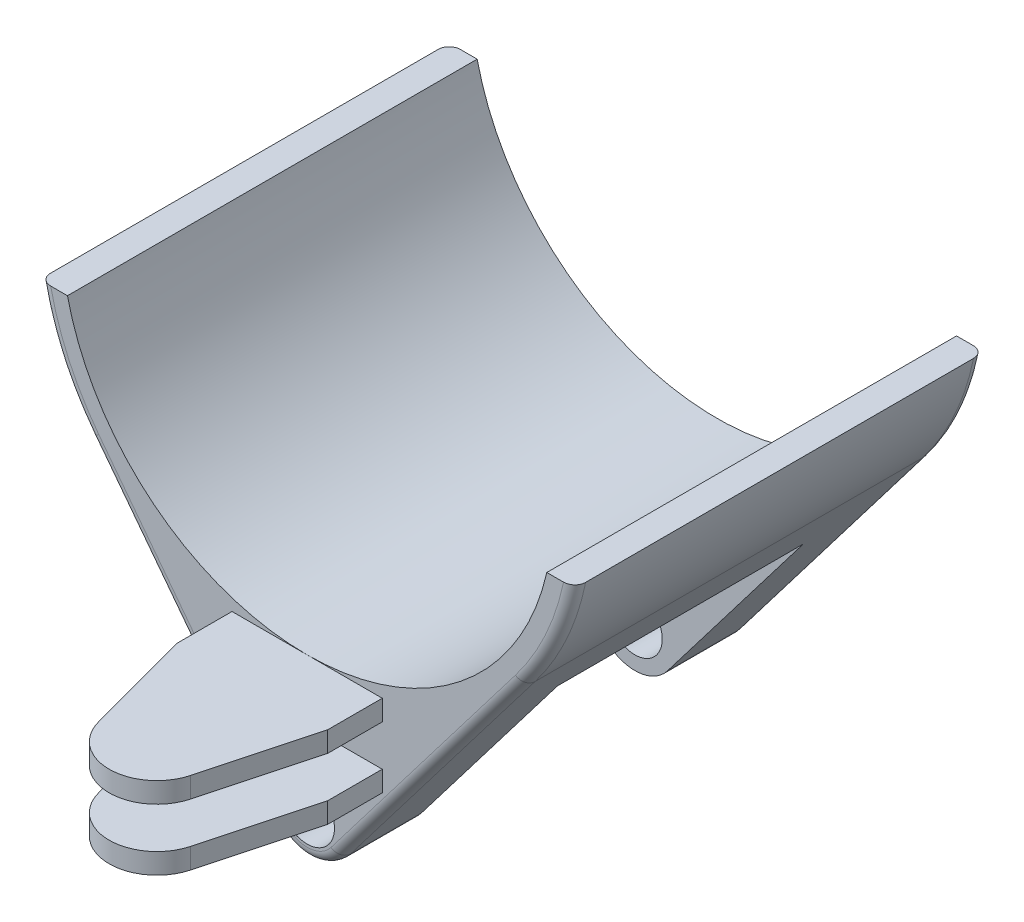
SolidWorks part; units mm, degrees
ref_plane "Front Plane" through (0, 0, 0) normal (0, 0, 1) x (1, 0, 0)
ref_plane "Top Plane" through (0, 0, 0) normal (0, 1, 0) x (1, 0, 0)
ref_plane "Right Plane" through (0, 0, 0) normal (1, 0, 0) x (0, 0, -1)
sketch "Sketch1" plane through (0, 0, 0) normal (0, 0, 1) x (1, 0, 0)
  line L0 (0, 0) -> (0, 420) construction
  line L1 (238.3778, 237.8571) -> (35.7567, -27.3214)
  line L2 (-35.7567, -27.3214) -> (-238.3778, 237.8571)
  line L3 (293.9388, 360) -> (263.2489, 360)
  line L4 (-263.2489, 360) -> (-293.9388, 360)
  arc A0 (-293.9388, 360) -> (-238.3778, 237.8571) centre (0, 420) ccw
  arc A1 (-263.2489, 360) -> (263.2489, 360) centre (0, 420) ccw
  arc A2 (-35.7567, -27.3214) -> (35.7567, -27.3214) centre (0, 0) ccw
  circle A3 centre (0, 0) radius 30
  arc A4 (238.3778, 237.8571) -> (293.9388, 360) centre (0, 420) ccw
  dimension "D1" = 600
  dimension "D2" = 540
  dimension "D3" = 60
  dimension "D4" = 90
  dimension "D5" = 60
  dimension "D6" = 360
extrude "Boss-Extrude2" add sketch "Sketch1" along normal mid plane 450
sketch "Sketch2" plane through (0, 0, 0) normal (0, 1, 0) x (1, 0, 0)
  line L0 (0, -225) -> (0, -390) construction
  line L1 (-263.2489, -225) -> (263.2489, -225) construction
  line L2 (82.5, -225) -> (-82.5, -225)
  line L3 (82.5, -225) -> (82.5, -285)
  line L4 (82.5, -285) -> (50.7097, -403.5933)
  line L5 (-82.5, -225) -> (-82.5, -285)
  line L6 (-82.5, -285) -> (-50.7097, -403.5933)
  arc A0 (-50.7097, -403.5933) -> (50.7097, -403.5933) centre (0, -390) ccw
  point P8 (0, -225)
  dimension "D1" = 165
  dimension "D5" = 105
  dimension "D2" = 60
  dimension "D3" = 60
  dimension "D4" = 165
extrude "Boss-Extrude3" add sketch "Sketch2" along normal blind 90 from offset 60
sketch "Sketch3" plane through (0, 0, 0) normal (1, 0, 0) x (0, 0, -1)
  line L0 (-225, 150) -> (-225, 60) construction
  line L1 (-225, 127.5) -> (-482.4052, 127.5)
  line L2 (-225, 127.5) -> (-225, 82.5)
  line L3 (-225, 82.5) -> (-482.4052, 82.5)
  line L4 (-482.4052, 127.5) -> (-482.4052, 82.5)
  line L5 (-403.5933, 150) -> (-442.5, 150) construction
  dimension "D1" = 45
  dimension "D2" = 22.5
extrude "Cut-Extrude1" cut sketch "Sketch3" against normal mid plane 303.8
sketch "Sketch4" plane through (0, 0, 0) normal (1, 0, 0) x (0, 0, -1)
  line L0 (-225, -27.3214) -> (-225, 237.8571) construction
  line L1 (-135, 142.5) -> (135, 142.5)
  line L2 (-135, 142.5) -> (-135, -224.9)
  line L3 (-135, -224.9) -> (135, -224.9)
  line L4 (135, 142.5) -> (135, -224.9)
  line L5 (-285, 150) -> (-225, 150) construction
  dimension "D1" = 90
  dimension "D2" = 90
  dimension "D3" = 7.5
extrude "Cut-Extrude2" cut sketch "Sketch4" against normal mid plane 843.7
chamfer "Chamfer1" distance 6 angle 45 2 edges at (165.5161, 142.5, 0) (-165.5161, 142.5, 0)
fillet "Fillet1" radius 6 2 edges at (0, 142.5, -135) (0, 142.5, 135)
fillet "Fillet2" radius 12 10 edges at (-273.075, 295.7823, -225) (-137.0672, 105.2679, -225) (0, -45, -225) (273.075, 295.7823, -225) (-273.075, 295.7823, 225) (-137.0672, 105.2679, 225) (0, -45, 225) (273.075, 295.7823, 225) (137.0672, 105.2679, -225) (137.0672, 105.2679, 225)
